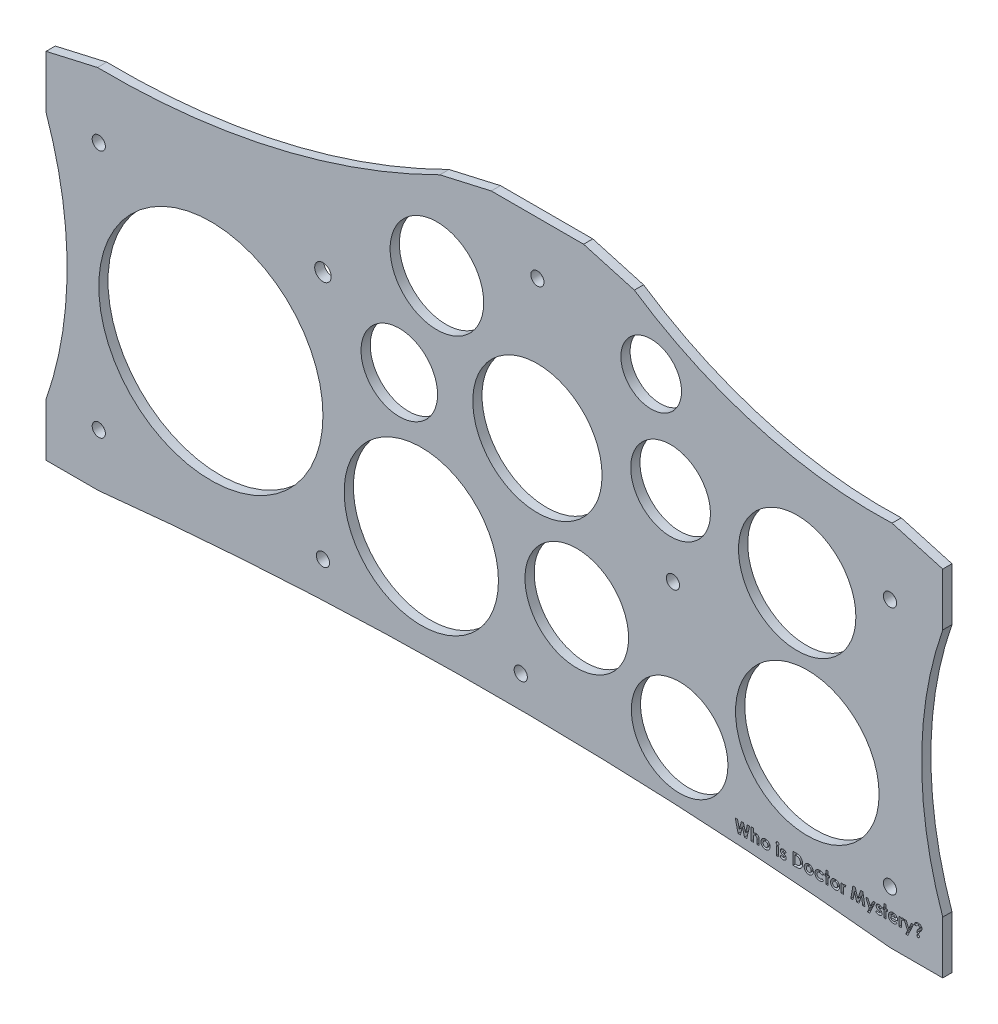
SolidWorks part; units mm, degrees
material "Cedar"
ref_plane "Front Plane" through (0, 0, 0) normal (0, 0, 1) x (1, 0, 0)
ref_plane "Top Plane" through (0, 0, 0) normal (0, 1, 0) x (1, 0, 0)
ref_plane "Right Plane" through (0, 0, 0) normal (1, 0, 0) x (0, 0, -1)
sketch "Sketch2" plane through (0, 0, 0) normal (0, 0, 1) x (1, 0, 0)
  line L1 (401.8817, -319.4711) -> (-233.1183, -319.4711)
  line L2 (401.8817, -319.4711) -> (401.8817, 315.5289)
  line L3 (401.8817, 315.5289) -> (-233.1183, 315.5289)
  line L4 (-233.1183, -319.4711) -> (-233.1183, 315.5289)
  line L5 (401.8817, -319.4711) -> (-233.1183, 315.5289) construction
  line L6 (401.8817, 315.5289) -> (-233.1183, -319.4711) construction
  point P0 (41.2053, 41.2053)
  dimension "D1" = 635
  dimension "D2" = 635
extrude "Boss-Extrude3" add sketch "Sketch2" along normal blind 4.445
sketch "Sketch3" plane through (0, 0, 0) normal (0, 0, -1) x (-1, 0, 0)
  circle A0 centre (-130.0265, 72.4535) radius 3.175
  circle A1 centre (-195.2881, -21.3837) radius 3.175
  circle A2 centre (-122.0047, -96.2659) radius 3.175
  circle A3 centre (-26.7547, -96.2659) radius 3.175
  circle A4 centre (-26.7547, 23.4697) radius 3.9751
  circle A5 centre (81.1953, -96.2659) radius 3.175
  circle A6 centre (-299.8047, -96.2659) radius 3.175
  circle A7 centre (81.1953, 23.4697) radius 3.175
  circle A8 centre (-299.8047, 23.4697) radius 3.175
  point P23 (-195.2881, -21.3837)
  point P24 (-130.0265, 72.4535)
  dimension "D1" = 6.35
  dimension "D2" = 6.35
  dimension "D3" = 6.35
  dimension "D4" = 6.35
  dimension "D5" = 7.9502
  dimension "D6" = 203.2
  dimension "D7" = 177.8
extrude "Cut-Extrude1" cut sketch "Sketch3" against normal through all
sketch "Sketch5" plane through (0, 0, 4.445) normal (0, 0, 1) x (1, 0, 0)
  line L0 (-106.5953, -121.6659) -> (325.2047, -121.6659)
  line L1 (-106.5953, -121.6659) -> (-106.5953, 48.8697)
  line L2 (-106.5953, 48.8697) -> (107.8015, 97.8535)
  line L3 (152.2515, 97.8535) -> (325.2047, 48.8697)
  line L4 (107.8015, 97.8535) -> (152.2515, 97.8535)
  line L7 (325.2047, 48.8697) -> (325.2047, -121.6659)
  line L9 (-233.1183, 315.5289) -> (401.8817, 315.5289)
  line L10 (-233.1183, 315.5289) -> (-233.1183, -319.4711)
  line L11 (-233.1183, -319.4711) -> (401.8817, -319.4711)
  line L12 (401.8817, 315.5289) -> (401.8817, -319.4711)
  circle A0 centre (122.0047, -96.2659) radius 3.175 construction
  circle A1 centre (-81.1953, -96.2659) radius 3.175 construction
  circle A3 centre (299.8047, 23.4697) radius 3.175 construction
  circle A4 centre (130.0265, 72.4535) radius 3.175 construction
  circle A5 centre (-81.1953, 23.4697) radius 3.175 construction
  point P18 (130.0265, 97.8535)
  point P19 (130.0265, 72.4535)
  dimension "D1" = 25.4
  dimension "D2" = 25.4
  dimension "D3" = 25.4
  dimension "D4" = 25.4
  dimension "D5" = 25.4
  dimension "D6" = 44.45
  dimension "D7" = 25.4
extrude "Cut-Extrude2" cut sketch "Sketch5" against normal through all
sketch "Sketch7" plane through (0, 0, 4.445) normal (0, 0, 1) x (1, 0, 0)
  line L0 (-81.1953, 23.4697) -> (26.7547, -96.2659) construction
  line L1 (-106.5953, -121.6659) -> (325.2047, -121.6659) construction
  line L2 (-106.5953, -121.6659) -> (-106.5953, 48.8697) construction
  line L3 (-106.5953, 48.8697) -> (107.8015, 97.8535) construction
  line L4 (152.2515, 97.8535) -> (325.2047, 48.8697) construction
  line L5 (325.2047, 48.8697) -> (325.2047, -121.6659) construction
  line L6 (-106.5953, -121.6659) -> (-106.5953, 48.8697) construction
  line L7 (-106.5953, 23.4697) -> (-106.5953, -96.2659)
  line L8 (-81.1953, -121.6659) -> (299.8047, -121.6659)
  line L9 (325.2047, -96.2659) -> (325.2047, 23.4697)
  line L10 (300.7659, 55.7913) -> (176.6903, 90.932)
  line L11 (83.0396, 92.1961) -> (-81.8334, 54.5271)
  circle A0 centre (-27.2203, -36.3981) radius 53.975
  circle A1 centre (74.1068, -63.0664) radius 37.1573
  circle A2 centre (81.6247, 49.3691) radius 22.534
  circle A3 centre (255.1128, 8.0341) radius 28.2634
  circle A4 centre (198.4958, -84.7267) radius 23.2677
  circle A5 centre (148.971, -55.571) radius 24.9537
  circle A6 centre (194.1429, 16.0636) radius 19.2001
  circle A7 centre (259.9863, -60.3834) radius 34.5622
  circle A8 centre (130.0295, 5.832) radius 31.1244
  circle A9 centre (184.8075, 59.9881) radius 14.5989
  circle A10 centre (63.5186, 0) radius 18.4298
  arc A11 (-81.1953, -121.6659) -> (299.8047, -121.6659) centre (109.3047, -1902.5234) cw
  arc A12 (-106.5953, -96.2659) -> (-106.5953, 23.4697) centre (-277.9008, -36.3981) ccw
  arc A13 (-81.8334, 54.5271) -> (83.0396, 92.1961) centre (-76.6442, 411.4647) ccw
  arc A14 (176.6903, 90.932) -> (300.7659, 55.7913) centre (293.0968, 265.3279) ccw
  arc A15 (325.2047, 23.4697) -> (325.2047, -96.2659) centre (496.5102, -36.3981) ccw
  point P14 (-27.2203, -36.3981)
  point P15 (-81.1953, -36.3981)
  point P28 (255.1128, 8.0341)
  point P54 (2.8661, 63.4568)
  point P57 (235.9595, 63.5861)
  point P58 (315.0447, -36.3981)
  point P59 (109.3047, -111.5059)
  point P60 (-96.4353, -36.3981)
  dimension "D1" = 25.4
  dimension "D2" = 10.16
  dimension "D3" = 25.4
  dimension "D4" = 25.4
  dimension "D5" = 25.4
  dimension "D6" = 25.4
  dimension "D7" = 25.4
  dimension "D8" = 25.4
  dimension "D9" = 25.4
  dimension "D10" = 25.4
  dimension "D11" = 25.4
  dimension "D12" = 25.4
  dimension "D13" = 10.16
  dimension "D14" = 10.16
  dimension "D15" = 10.16
  dimension "D16" = 10.16
extrude "Cut-Extrude3" cut sketch "Sketch7" against normal through all
sketch "Sketch8" plane through (0, 0, 4.445) normal (0, 0, 1) x (1, 0, 0)
  line L0 (225.1982, -110.7) -> (325.2047, -110.7) construction
  line L1 (325.2047, -96.2659) -> (325.2047, -121.6659) construction
  text T0 "Who is Doctor Mystery?" font "Century Gothic" height in points 22
extrude "Cut-Extrude4" cut sketch "Sketch8" against normal blind 2.54
